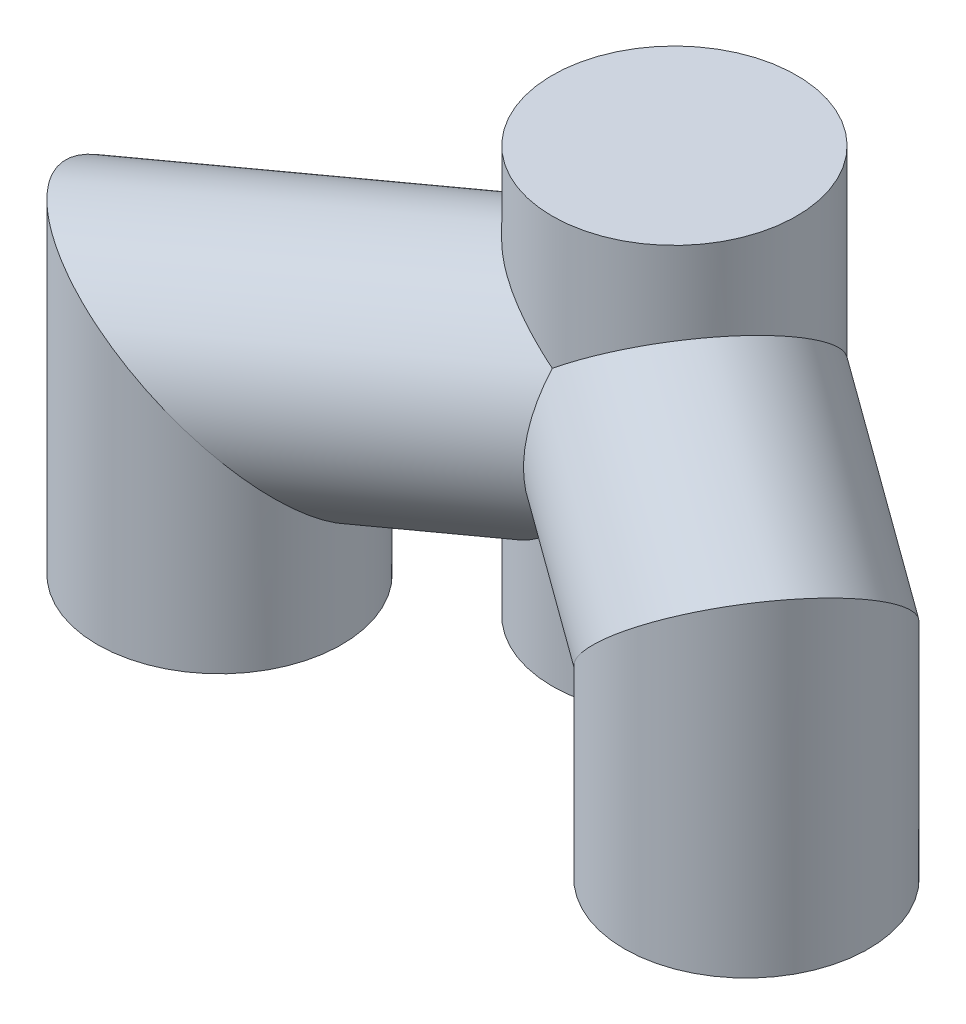
SolidWorks part; units mm, degrees
ref_plane "Front Plane" through (0, 0, 0) normal (0, 0, 1) x (1, 0, 0)
ref_plane "Top Plane" through (0, 0, 0) normal (0, 1, 0) x (1, 0, 0)
ref_plane "Right Plane" through (0, 0, 0) normal (1, 0, 0) x (0, 0, -1)
sketch "Sketch1" plane through (0, 0, 0) normal (0, 1, 0) x (1, 0, 0)
  circle A0 centre (0, 0) radius 1.5
  dimension "D1" = 3
sketch "Sketch2" plane through (0, 0, 0) normal (0, 1, 0) x (1, 0, 0)
  line L0 (9.3879, 0) -> (-9.3879, 0) construction
  line L1 (0, 12.3453) -> (0, -12.3453) construction
  line L2 (0, 0) -> (3.2361, -2.3511)
  line L3 (0, 0) -> (-3.2361, -2.3511)
  circle A0 centre (-3.2361, -2.3511) radius 1.5
  circle A1 centre (3.2361, -2.3511) radius 1.5
  point P5 (0, 0)
  point P9 (0, 0)
  dimension "D5" = 3
  dimension "D6" = 3
  dimension "D1" = 36
  dimension "D2" = 4
  dimension "D3" = 36
  dimension "D4" = 4
ref_plane "Plane2" through (0, 0, 0) normal (-0.5878, 0, -0.809) x (-0.809, 0, 0.5878)
ref_plane "Plane3" through (0, 0, 0) normal (-0.5878, 0, 0.809) x (0.809, 0, 0.5878)
sketch "Sketch3" plane through (0, 0, 0) normal (-0.5878, 0, -0.809) x (-0.809, 0, 0.5878)
  line L0 (4, 0) -> (4, 2.5)
  line L1 (4, 2.5) -> (0, 2.5)
  dimension "D1" = 2.5
  dimension "D2" = 4
sweep "Sweep1" add profiles "Sketch2" path "Sketch3"
sketch "Sketch5" plane through (0, 0, 0) normal (0, 1, 0) x (1, 0, 0)
  line L0 (0, 0) -> (3.2361, -2.3511) construction
  line L1 (0, 0) -> (-3.2361, -2.3511) construction
  line L2 (0, 0) -> (3.2361, -2.3511)
  line L3 (0, 0) -> (-3.2361, -2.3511)
  circle A0 centre (0, 0) radius 1.5 construction
  circle A1 centre (0, 0) radius 1.5
  circle A3 centre (3.2361, -2.3511) radius 1.5
  circle A4 centre (3.2361, -2.3511) radius 1.5
  circle A5 centre (-3.2361, -2.3511) radius 1.5
  circle A6 centre (-3.2361, -2.3511) radius 1.5
  dimension "D1" = 0
  dimension "D2" = 0
sketch "Sketch6" plane through (0, 0, 0) normal (-0.5878, 0, 0.809) x (0.809, 0, 0.5878)
  line L0 (4, 0) -> (4, 2.5)
  line L1 (4, 2.5) -> (0, 2.5)
  dimension "D1" = 2.5
  dimension "D2" = 4
sweep "Sweep2" add profiles "Sketch5" path "Sketch6"
extrude "Boss-Extrude1" add sketch "Sketch1" along normal blind 5
